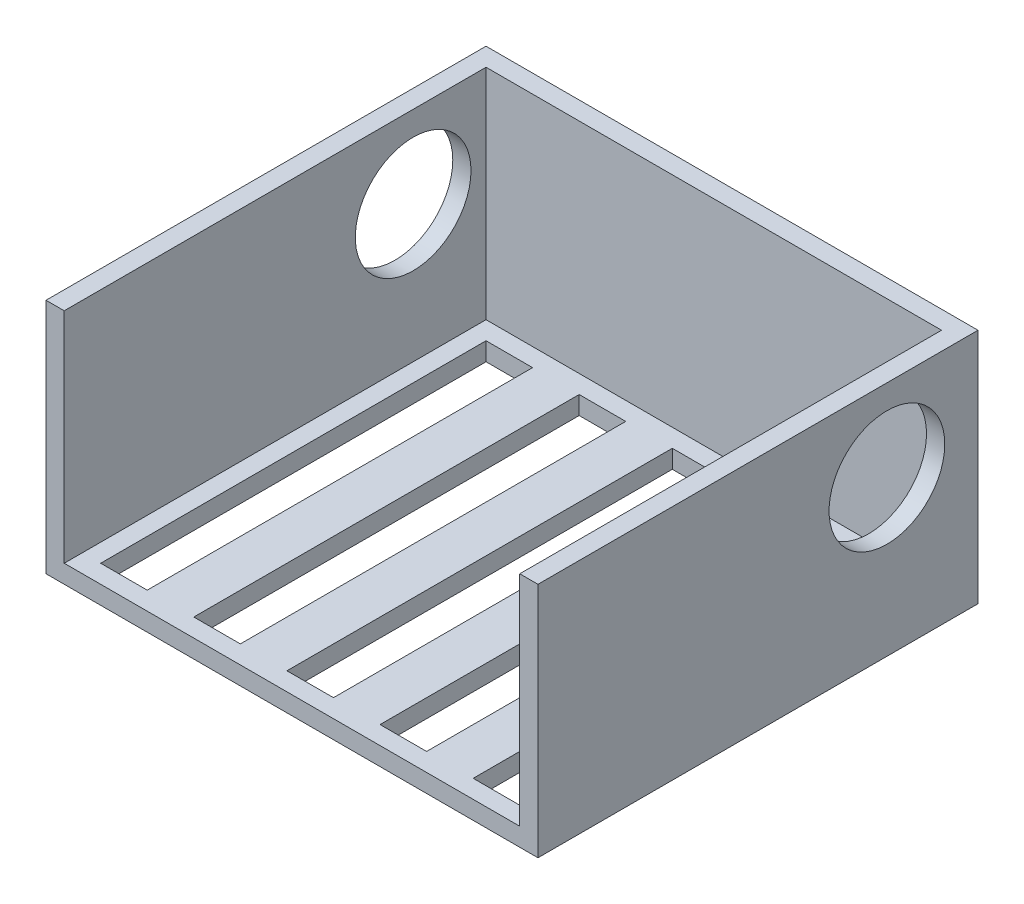
SolidWorks part; units mm, degrees
ref_plane "Alzado" through (0, 0, 0) normal (0, 0, 1) x (1, 0, 0)
ref_plane "Planta" through (0, 0, 0) normal (0, 1, 0) x (1, 0, 0)
ref_plane "Vista lateral" through (0, 0, 0) normal (1, 0, 0) x (0, 0, -1)
sketch "Croquis1" plane through (0, 0, 0) normal (0, 1, 0) x (1, 0, 0)
  line L0 (2, 2) -> (-52, 2)
  line L1 (0, 0) -> (-50, 0)
  line L2 (0, 0) -> (0, -46.3)
  line L3 (0, -46.3) -> (-50, -46.3)
  line L4 (-50, 0) -> (-50, -46.3)
  line L5 (-52, 2) -> (-52, -48.3)
  line L6 (2, -48.3) -> (-52, -48.3)
  line L7 (2, 2) -> (2, -48.3)
  dimension "D1" = 50
  dimension "D2" = 46.3
  dimension "D3" = 2
extrude "Saliente-Extruir1" add sketch "Croquis1" along normal blind 24
sketch "Croquis2" plane through (0, 0, 0) normal (0, -1, 0) x (1, 0, 0)
  line L4 (2, -2) -> (2, 48.3)
  line L5 (2, 48.3) -> (-52, 48.3)
  line L6 (-52, 48.3) -> (-52, -2)
  line L7 (-52, -2) -> (2, -2)
  line L8 (2, -2) -> (2, 48.3)
  line L9 (2, 48.3) -> (-52, 48.3)
  line L10 (-52, 48.3) -> (-52, -2)
  line L11 (-52, -2) -> (2, -2)
  dimension "D1" = 0
extrude "Saliente-Extruir2" add sketch "Croquis2" along normal blind 2
sketch "Croquis6" plane through (-52, 0, 0) normal (-1, 0, 0) x (0, 0, 1)
  line L0 (46.3, 24) -> (46.3, 0) construction
  line L1 (46.3, 24) -> (46.3, 0)
  line L2 (46.3, 0) -> (46.3, -2)
  line L3 (48.3, -2) -> (-2, -2) construction
  line L4 (46.3, -2) -> (48.3, -2)
  line L5 (48.3, -2) -> (48.3, 24)
  line L6 (48.3, 24) -> (46.3, 24)
extrude "Cortar-Extruir4" cut sketch "Croquis6" against normal up to surface (54 mm away) up to face at (2, 11, 23.15)
sketch "Croquis7" plane through (0, 0, 0) normal (0, 1, 0) x (1, 0, 0)
  line L10 (-42.8889, -2) -> (-42.8889, -44.3)
  line L11 (-37.7778, -2) -> (-37.7778, -44.3)
  line L12 (-32.6667, -2) -> (-32.6667, -44.3)
  line L13 (-27.5556, -2) -> (-27.5556, -44.3)
  line L14 (-2, -44.3) -> (-2, -2)
  line L15 (-2, -2) -> (-48, -2)
  line L16 (-48, -2) -> (-48, -44.3)
  line L17 (-48, -44.3) -> (-2, -44.3)
  line L18 (-2, -44.3) -> (-2, -2)
  line L19 (-2, -2) -> (-7.1111, -2)
  line L20 (-48, -2) -> (-48, -44.3)
  line L21 (-48, -44.3) -> (-42.8889, -44.3)
  line L22 (-22.4444, -2) -> (-22.4444, -44.3)
  line L23 (-17.3333, -2) -> (-17.3333, -44.3)
  line L24 (-12.2222, -2) -> (-12.2222, -44.3)
  line L25 (-7.1111, -2) -> (-7.1111, -44.3)
  line L26 (-2, -2) -> (-2, -44.3)
  line L27 (-48, -2) -> (-42.8889, -2)
  line L28 (-42.8889, -2) -> (-48, -2)
  line L29 (-37.7778, -44.3) -> (-32.6667, -44.3)
  line L30 (-27.5556, -44.3) -> (-22.4444, -44.3)
  line L31 (-17.3333, -44.3) -> (-12.2222, -44.3)
  line L32 (-7.1111, -44.3) -> (-2, -44.3)
  line L33 (-12.2222, -2) -> (-17.3333, -2)
  line L34 (-22.4444, -2) -> (-27.5556, -2)
  line L35 (-32.6667, -2) -> (-37.7778, -2)
  dimension "D3" = 5.1111
  dimension "D1" = 2
  dimension "D2" = 10
extrude "Cortar-Extruir5" cut sketch "Croquis7" against normal up to next contours L27 L20 L21 L10 | L12 L35 L11 L29 | L24 L33 L23 L31 | L25 L32 L18 L19 | L13 L30 L22 L34
ref_plane "Plano1" through (-25, 0, 0) normal (1, 0, 0) x (0, 0, -1)
sketch "Croquis8" plane through (-25, 0, 0) normal (1, 0, 0) x (0, 0, -1)
  line L0 (0, 24) -> (-46.3, 24) construction
  line L1 (0, 24) -> (-46.3, 24) construction
  line L2 (0, 15) -> (-8, 15) construction
  line L4 (0, 15) -> (0, 24) construction
  circle A0 centre (-8, 15) radius 6.35
  dimension "D2" = 12.7
  dimension "D1" = 9
  dimension "D3" = 8
extrude "Cortar-Extruir6" cut sketch "Croquis8" against normal through all both and the other way through all
